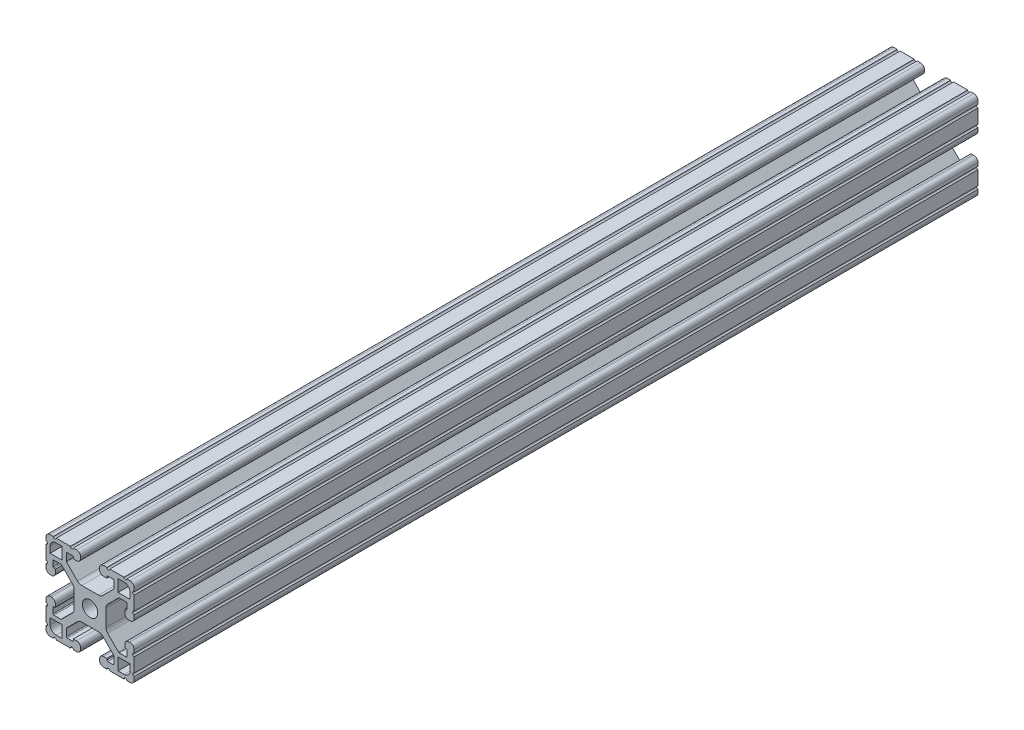
SolidWorks part; units mm, degrees
ref_plane "Front Plane" through (0, 0, 0) normal (0, 0, 1) x (1, 0, 0)
ref_plane "Top Plane" through (0, 0, 0) normal (0, 1, 0) x (1, 0, 0)
ref_plane "Right Plane" through (0, 0, 0) normal (1, 0, 0) x (0, 0, -1)
sketch "Sketch1" plane through (0, 0, 0) normal (0, 0, 1) x (1, 0, 0)
  line L0 (0, -19.05) -> (0, 19.05) construction
  line L1 (19.05, 0) -> (-19.05, 0) construction
  line L2 (4.064, 19.05) -> (-4.064, 19.05) construction
  line L3 (0, -6.858) -> (0, 6.858) construction
  line L4 (-4.064, 19.05) -> (-4.064, 14.986) construction
  line L5 (19.05, -10.287) -> (19.05, 10.287) construction
  line L6 (0, -3.302) -> (0, 3.302) construction
  point P4 (0, 0)
  point P8 (0, 0)
  point P11 (0, 19.05)
  point P14 (0, 0)
  point P18 (19.05, 0)
  point P21 (0, 0)
sketch "Sketch2" plane through (0, 0, 0) normal (1, 0, 0) x (0, 0, -1)
  line L0 (-457.2, 0) -> (457.2, 0) construction
  point P4 (0, 0)
  dimension "Length" = 914.4
sketch "Sketch3" plane through (0, 0, 0) normal (0, 0, 1) x (1, 0, 0)
  line L1 (19.05, -19.05) -> (-19.05, -19.05)
  line L2 (19.05, -19.05) -> (19.05, 19.05)
  line L3 (19.05, 19.05) -> (-19.05, 19.05)
  line L4 (-19.05, -19.05) -> (-19.05, 19.05)
  line L5 (19.05, -19.05) -> (-19.05, 19.05) construction
  line L6 (19.05, 19.05) -> (-19.05, -19.05) construction
  point P0 (0, 0)
extrude "Boss-Extrude1" add sketch "Sketch3" along normal up to vertex (457.2 mm away) and the other way up to vertex (457.2 mm away) up to point (0, 0, 457.2) other way up to point (0, 0, -457.2)
sketch "Sketch4" plane through (0, 0, 457.2) normal (0, 0, 1) x (1, 0, 0)
  line L4 (4.064, 14.986) -> (4.064, 19.05)
  line L5 (7.239, 14.986) -> (4.064, 14.986)
  line L6 (19.05, 0) -> (-19.05, 0) construction
  line L7 (4.7027, 6.858) -> (-4.7027, 6.858)
  line L8 (-4.7027, 6.858) -> (-10.287, 12.4423)
  line L37 (-19.05, 19.05) -> (-19.05, -19.05) construction
  line L38 (-19.05, -19.05) -> (19.05, -19.05) construction
  line L39 (-10.287, 12.4423) -> (-10.287, 16.002)
  line L40 (-10.287, 16.002) -> (-7.239, 16.002)
  line L41 (-7.239, 16.002) -> (-7.239, 14.986)
  line L42 (-7.239, 14.986) -> (-4.064, 14.986)
  line L43 (-4.064, 14.986) -> (-4.064, 19.05)
  line L44 (-4.064, 19.05) -> (4.064, 19.05)
  line L45 (0, 19.05) -> (0, 0) construction
  line L46 (-19.05, 19.05) -> (0, 0) construction
  line L47 (7.239, 16.002) -> (7.239, 14.986)
  line L48 (10.287, 16.002) -> (7.239, 16.002)
  line L49 (10.287, 12.4423) -> (10.287, 16.002)
  line L50 (4.7027, 6.858) -> (10.287, 12.4423)
  line L51 (-19.05, 0) -> (19.05, 0) construction
  line L52 (4.7027, -6.858) -> (10.287, -12.4423)
  line L53 (10.287, -12.4423) -> (10.287, -16.002)
  line L54 (10.287, -16.002) -> (7.239, -16.002)
  line L55 (7.239, -16.002) -> (7.239, -14.986)
  line L56 (-4.064, -19.05) -> (4.064, -19.05)
  line L57 (-4.064, -14.986) -> (-4.064, -19.05)
  line L58 (-7.239, -14.986) -> (-4.064, -14.986)
  line L59 (-7.239, -16.002) -> (-7.239, -14.986)
  line L60 (-10.287, -16.002) -> (-7.239, -16.002)
  line L61 (-10.287, -12.4423) -> (-10.287, -16.002)
  line L62 (-4.7027, -6.858) -> (-10.287, -12.4423)
  line L63 (4.7027, -6.858) -> (-4.7027, -6.858)
  line L64 (7.239, -14.986) -> (4.064, -14.986)
  line L65 (4.064, -14.986) -> (4.064, -19.05)
  line L66 (-6.858, -4.7027) -> (-12.4423, -10.287)
  line L67 (-12.4423, -10.287) -> (-16.002, -10.287)
  line L68 (-16.002, -10.287) -> (-16.002, -7.239)
  line L69 (-16.002, -7.239) -> (-14.986, -7.239)
  line L70 (-19.05, 4.064) -> (-19.05, -4.064)
  line L71 (-14.986, 4.064) -> (-19.05, 4.064)
  line L72 (-14.986, 7.239) -> (-14.986, 4.064)
  line L73 (-16.002, 7.239) -> (-14.986, 7.239)
  line L74 (-16.002, 10.287) -> (-16.002, 7.239)
  line L75 (-12.4423, 10.287) -> (-16.002, 10.287)
  line L76 (-6.858, 4.7027) -> (-12.4423, 10.287)
  line L77 (-6.858, -4.7027) -> (-6.858, 4.7027)
  line L78 (-14.986, -7.239) -> (-14.986, -4.064)
  line L79 (-14.986, -4.064) -> (-19.05, -4.064)
  line L80 (14.986, -4.064) -> (19.05, -4.064)
  line L81 (14.986, -7.239) -> (14.986, -4.064)
  line L82 (6.858, -4.7027) -> (6.858, 4.7027)
  line L83 (6.858, 4.7027) -> (12.4423, 10.287)
  line L84 (12.4423, 10.287) -> (16.002, 10.287)
  line L85 (16.002, 10.287) -> (16.002, 7.239)
  line L86 (16.002, 7.239) -> (14.986, 7.239)
  line L87 (14.986, 7.239) -> (14.986, 4.064)
  line L88 (14.986, 4.064) -> (19.05, 4.064)
  line L89 (19.05, 4.064) -> (19.05, -4.064)
  line L90 (16.002, -7.239) -> (14.986, -7.239)
  line L91 (16.002, -10.287) -> (16.002, -7.239)
  line L92 (12.4423, -10.287) -> (16.002, -10.287)
  line L93 (6.858, -4.7027) -> (12.4423, -10.287)
  line L94 (19.05, -19.05) -> (19.05, 19.05) construction
  line L95 (12.065, 17.272) -> (17.272, 17.272)
  line L96 (12.065, 17.272) -> (12.065, 12.065)
  line L97 (12.065, 12.065) -> (17.272, 12.065)
  line L98 (17.272, 17.272) -> (17.272, 12.065)
  line L99 (19.05, 19.05) -> (-19.05, 19.05) construction
  line L100 (17.272, -17.272) -> (17.272, -12.065)
  line L101 (12.065, -17.272) -> (17.272, -17.272)
  line L102 (12.065, -17.272) -> (12.065, -12.065)
  line L103 (12.065, -12.065) -> (17.272, -12.065)
  line L104 (-17.272, 17.272) -> (-17.272, 12.065)
  line L105 (-12.065, 12.065) -> (-17.272, 12.065)
  line L106 (-12.065, 17.272) -> (-12.065, 12.065)
  line L107 (-12.065, 17.272) -> (-17.272, 17.272)
  line L108 (-12.065, -12.065) -> (-17.272, -12.065)
  line L109 (-12.065, -17.272) -> (-12.065, -12.065)
  line L110 (-12.065, -17.272) -> (-17.272, -17.272)
  line L111 (-17.272, -17.272) -> (-17.272, -12.065)
  circle A5 centre (0, 0) radius 3.302
  point P21 (0, 6.858)
  point P23 (0, -6.858)
  point P38 (-6.858, 0)
  point P53 (6.858, 0)
  dimension "D1" = 20.574
  dimension "D2" = 3.048
  dimension "D3" = 3.048
  dimension "D4" = 3.048
  dimension "D5" = 1.778
  dimension "D6" = 1.778
  dimension "D7" = 1.778
extrude "Cut-Extrude1" cut sketch "Sketch4" against normal through all
sketch "Sketch5" plane through (0, 0, 457.2) normal (0, 0, 1) x (1, 0, 0)
  line L4 (-4.064, 19.05) -> (-19.05, 19.05) construction
  line L26 (-19.05, 19.05) -> (-19.05, 4.064) construction
  line L27 (-15.875, 19.05) -> (-14.605, 19.05)
  line L28 (-8.509, 19.05) -> (-7.239, 19.05)
  line L29 (-19.05, 15.875) -> (-19.05, 14.605)
  line L30 (-19.05, 8.509) -> (-19.05, 7.239)
  line L31 (8.509, 19.05) -> (7.239, 19.05)
  line L32 (15.875, 19.05) -> (14.605, 19.05)
  line L33 (19.05, 15.875) -> (19.05, 14.605)
  line L34 (19.05, 8.509) -> (19.05, 7.239)
  line L35 (19.05, -8.509) -> (19.05, -7.239)
  line L36 (19.05, -15.875) -> (19.05, -14.605)
  line L37 (15.875, -19.05) -> (14.605, -19.05)
  line L38 (8.509, -19.05) -> (7.239, -19.05)
  line L39 (-8.509, -19.05) -> (-7.239, -19.05)
  line L40 (-15.875, -19.05) -> (-14.605, -19.05)
  line L41 (-19.05, -15.875) -> (-19.05, -14.605)
  line L42 (-19.05, -8.509) -> (-19.05, -7.239)
  line L43 (19.05, 19.05) -> (4.064, 19.05) construction
  line L44 (19.05, 4.064) -> (19.05, 19.05) construction
  line L48 (-14.986, 4.064) -> (-19.05, 4.064) construction
  line L49 (-4.064, 14.986) -> (-4.064, 19.05) construction
  arc A8 (-15.875, 19.05) -> (-14.605, 19.05) centre (-15.24, 19.05) ccw
  arc A9 (-8.509, 19.05) -> (-7.239, 19.05) centre (-7.874, 19.05) ccw
  arc A10 (-19.05, 14.605) -> (-19.05, 15.875) centre (-19.05, 15.24) ccw
  arc A11 (-19.05, 7.239) -> (-19.05, 8.509) centre (-19.05, 7.874) ccw
  arc A12 (7.239, 19.05) -> (8.509, 19.05) centre (7.874, 19.05) ccw
  arc A13 (14.605, 19.05) -> (15.875, 19.05) centre (15.24, 19.05) ccw
  arc A14 (19.05, 15.875) -> (19.05, 14.605) centre (19.05, 15.24) ccw
  arc A15 (19.05, 8.509) -> (19.05, 7.239) centre (19.05, 7.874) ccw
  arc A16 (19.05, -7.239) -> (19.05, -8.509) centre (19.05, -7.874) ccw
  arc A17 (19.05, -14.605) -> (19.05, -15.875) centre (19.05, -15.24) ccw
  arc A18 (15.875, -19.05) -> (14.605, -19.05) centre (15.24, -19.05) ccw
  arc A19 (8.509, -19.05) -> (7.239, -19.05) centre (7.874, -19.05) ccw
  arc A20 (-7.239, -19.05) -> (-8.509, -19.05) centre (-7.874, -19.05) ccw
  arc A21 (-14.605, -19.05) -> (-15.875, -19.05) centre (-15.24, -19.05) ccw
  arc A22 (-19.05, -15.875) -> (-19.05, -14.605) centre (-19.05, -15.24) ccw
  arc A23 (-19.05, -8.509) -> (-19.05, -7.239) centre (-19.05, -7.874) ccw
  dimension "D2" = 0.635
  dimension "D4" = 3.81
  dimension "D5" = 3.81
  dimension "D1" = 3.81
  dimension "D3" = 3.81
  dimension "D7" = 4
extrude "Cut-Extrude2" cut sketch "Sketch5" against normal through all
fillet "Fillet1" radius 2.54 12 edges at (-6.858, 4.7027, 0) (-6.858, -4.7027, 0) (4.7027, -6.858, 0) (-4.7027, -6.858, 0) (6.858, -4.7027, 0) (6.858, 4.7027, 0) (4.7027, 6.858, 0) (-4.7027, 6.858, 0) (-17.272, 17.272, 0) (17.272, 17.272, 0) (17.272, -17.272, 0) (-17.272, -17.272, 0)
fillet "Fillet2" radius 1.778 20 edges at (19.05, -19.05, 0) (19.05, 19.05, 0) (-19.05, -19.05, 0) (-19.05, 19.05, 0) (-14.986, 4.064, 0) (-19.05, 4.064, 0) (-19.05, -4.064, 0) (-14.986, -4.064, 0) (-4.064, -19.05, 0) (-4.064, -14.986, 0) (4.064, -14.986, 0) (4.064, -19.05, 0) (19.05, -4.064, 0) (14.986, -4.064, 0) (19.05, 4.064, 0) (14.986, 4.064, 0) (4.064, 14.986, 0) (4.064, 19.05, 0) (-4.064, 19.05, 0) (-4.064, 14.986, 0)
fillet "Fillet3" radius 0.3969 24 edges at (-14.986, -7.239, 0) (-16.002, -10.287, 0) (-12.4423, -10.287, 0) (-12.4423, 10.287, 0) (-16.002, 7.239, 0) (-16.002, 10.287, 0) (-10.287, 12.4423, 0) (-7.239, 16.002, 0) (-10.287, 16.002, 0) (10.287, 16.002, 0) (7.239, 16.002, 0) (10.287, 12.4423, 0) (16.002, 10.287, 0) (12.4423, 10.287, 0) (16.002, 7.239, 0) (16.002, -7.239, 0) (16.002, -10.287, 0) (12.4423, -10.287, 0) (10.287, -12.4423, 0) (10.287, -16.002, 0) (7.239, -16.002, 0) (-7.239, -16.002, 0) (-10.287, -12.4423, 0) (-10.287, -16.002, 0)
sketch "Sketch6" plane through (0, 0, 457.2) normal (0, 0, 1) x (1, 0, 0)
  line L1 (21.2862, -22.4294) -> (-21.2862, -22.4294)
  line L2 (21.2862, -22.4294) -> (21.2862, 22.4294)
  line L3 (21.2862, 22.4294) -> (-21.2862, 22.4294)
  line L4 (-21.2862, -22.4294) -> (-21.2862, 22.4294)
  line L5 (21.2862, -22.4294) -> (-21.2862, 22.4294) construction
  line L6 (21.2862, 22.4294) -> (-21.2862, -22.4294) construction
  point P0 (0, 0)
extrude "Cut-Extrude3" cut sketch "Sketch6" against normal blind 549.8
equation "\"D4@Sketch5\"=\"D3@Sketch5\""
equation "\"D5@Sketch5\"=\"D4@Sketch5\""
equation "\"D1@Sketch4\"=\"Opening Width@Sketch1\""
